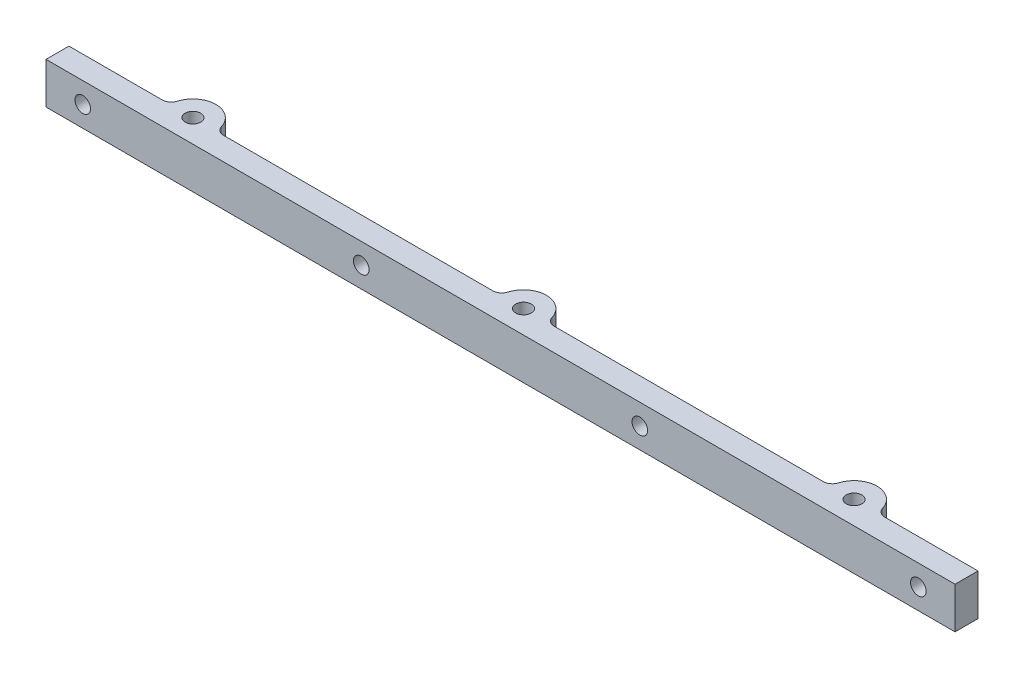
SolidWorks part; units mm, degrees
ref_plane "Plan de face" through (0, 0, 0) normal (0, 0, 1) x (1, 0, 0)
ref_plane "Plan de dessus" through (0, 0, 0) normal (0, 1, 0) x (1, 0, 0)
ref_plane "Plan de droite" through (0, 0, 0) normal (1, 0, 0) x (0, 0, -1)
sketch "Esquisse1" plane through (0, 0, 0) normal (0, 1, 0) x (1, 0, 0)
  line L0 (-99, 2.5) -> (-77, 2.5)
  line L2 (-99, 2.5) -> (-99, -2.5)
  line L3 (-99, -2.5) -> (99, -2.5)
  line L4 (99, 2.5) -> (99, -2.5)
  line L5 (-99, 2.5) -> (99, -2.5) construction
  line L6 (-99, -2.5) -> (99, 2.5) construction
  line L7 (-67, 2.5) -> (-5, 2.5)
  line L8 (5, 2.5) -> (67, 2.5)
  line L9 (77, 2.5) -> (99, 2.5)
  arc A0 (-77, 2.5) -> (-67, 2.5) centre (-72, 2.5) cw
  arc A1 (-5, 2.5) -> (5, 2.5) centre (0, 2.5) cw
  arc A2 (67, 2.5) -> (77, 2.5) centre (72, 2.5) cw
  point P0 (0, 0)
  dimension "D3" = 5
  dimension "D1" = 198
  dimension "D2" = 5
  dimension "D4" = 22
extrude "Boss.-Extru.1" add sketch "Esquisse1" along normal blind 9
hole_wizard "Dégagement M31" positions "Esquisse3" profile "Esquisse4" hole size "M3" standard "Ansi Metric" end condition up to next
sketch "Esquisse3" plane through (0, 9, 0) normal (0, 1, 0) x (1, 0, 0)
  point P0 (-72, 2.5)
  point P3 (0, 2.5)
  point P6 (72, 2.5)
sketch "Esquisse4" plane through (-72, 9, -2.5) normal (1, 0, 0) x (0, 0, 1)
  line L0 (0, 0) -> (0, 9)
  line L1 (0, 9) -> (1.7, 9)
  line L2 (1.7, 9) -> (1.7, 0)
  line L5 (1.7, 0) -> (0, 0)
  line L11 (0, -6.35) -> (0, 107.95) construction
  dimension "Diamètre du perçage jusqu'au prochain" = 3.4
  dimension "Profondeur du perçage jusqu'au prochain" = 9
sketch "Esquisse5" plane through (0, 0, 0) normal (0, -1, 0) x (1, 0, 0)
  line L1 (70.4123, -5.25) -> (73.5877, -5.25)
  line L2 (73.5877, -5.25) -> (75.1754, -2.5)
  line L3 (75.1754, -2.5) -> (73.5877, 0.25)
  line L4 (73.5877, 0.25) -> (70.4123, 0.25)
  line L5 (70.4123, 0.25) -> (68.8246, -2.5)
  line L6 (68.8246, -2.5) -> (70.4123, -5.25)
  line L7 (-1.5877, -5.25) -> (1.5877, -5.25)
  line L8 (1.5877, -5.25) -> (3.1754, -2.5)
  line L9 (3.1754, -2.5) -> (1.5877, 0.25)
  line L10 (1.5877, 0.25) -> (-1.5877, 0.25)
  line L11 (-1.5877, 0.25) -> (-3.1754, -2.5)
  line L12 (-3.1754, -2.5) -> (-1.5877, -5.25)
  line L13 (-73.5877, -5.25) -> (-70.4123, -5.25)
  line L14 (-70.4123, -5.25) -> (-68.8246, -2.5)
  line L15 (-68.8246, -2.5) -> (-70.4123, 0.25)
  line L16 (-70.4123, 0.25) -> (-73.5877, 0.25)
  line L17 (-73.5877, 0.25) -> (-75.1754, -2.5)
  line L18 (-75.1754, -2.5) -> (-73.5877, -5.25)
  circle A0 centre (72, -2.5) radius 2.75 construction
  circle A1 centre (0, -2.5) radius 2.75 construction
  circle A2 centre (-72, -2.5) radius 2.75 construction
  dimension "D1" = 5.5
extrude "Enlèv. mat.-Extru.1" cut sketch "Esquisse5" against normal blind 2.5
sketch "Esquisse6" plane through (0, 0, 2.5) normal (0, 0, 1) x (1, 0, 0)
  line L0 (-99, 0) -> (-91, 4.5) construction
  line L1 (-91, 4.5) -> (-30.3333, 4.5) construction
  line L2 (91, 4.5) -> (99, 0) construction
  line L3 (-30.3333, 4.5) -> (30.3333, 4.5) construction
  line L4 (30.3333, 4.5) -> (91, 4.5) construction
  line L5 (-99, 9) -> (-91, 4.5) construction
  line L6 (-99, 9) -> (-99, 0) construction
  dimension "D1" = 8
hole_wizard "Dégagement M32" positions "Esquisse7" profile "Esquisse8" hole size "M3" standard "Ansi Metric" end condition up to next
sketch "Esquisse7" plane through (0, 0, 2.5) normal (0, 0, 1) x (1, 0, 0)
  point P0 (-91, 4.5)
  point P3 (-30.3333, 4.5)
  point P6 (30.3333, 4.5)
  point P9 (91, 4.5)
sketch "Esquisse8" plane through (-91, 4.5, 2.5) normal (1, 0, 0) x (0, -1, 0)
  line L0 (0, 0) -> (0, 5)
  line L1 (0, 5) -> (1.7, 5)
  line L2 (1.7, 5) -> (1.7, 0)
  line L5 (1.7, 0) -> (0, 0)
  line L11 (0, -6.35) -> (0, 107.95) construction
  dimension "Diamètre du perçage jusqu'au prochain" = 3.4
  dimension "Profondeur du perçage jusqu'au prochain" = 5
sketch "Esquisse9" plane through (0, 0, -2.5) normal (0, 0, -1) x (-1, 0, 0)
  line L1 (-89.4123, 7.25) -> (-92.5877, 7.25)
  line L2 (-92.5877, 7.25) -> (-94.1754, 4.5)
  line L3 (-94.1754, 4.5) -> (-92.5877, 1.75)
  line L4 (-92.5877, 1.75) -> (-89.4123, 1.75)
  line L5 (-89.4123, 1.75) -> (-87.8246, 4.5)
  line L6 (-87.8246, 4.5) -> (-89.4123, 7.25)
  line L7 (-28.7456, 7.25) -> (-31.921, 7.25)
  line L8 (-31.921, 7.25) -> (-33.5088, 4.5)
  line L9 (-33.5088, 4.5) -> (-31.921, 1.75)
  line L10 (-31.921, 1.75) -> (-28.7456, 1.75)
  line L11 (-28.7456, 1.75) -> (-27.1579, 4.5)
  line L12 (-27.1579, 4.5) -> (-28.7456, 7.25)
  line L13 (31.921, 7.25) -> (28.7456, 7.25)
  line L14 (28.7456, 7.25) -> (27.1579, 4.5)
  line L15 (27.1579, 4.5) -> (28.7456, 1.75)
  line L16 (28.7456, 1.75) -> (31.921, 1.75)
  line L17 (31.921, 1.75) -> (33.5088, 4.5)
  line L18 (33.5088, 4.5) -> (31.921, 7.25)
  line L19 (92.5877, 7.25) -> (89.4123, 7.25)
  line L20 (89.4123, 7.25) -> (87.8246, 4.5)
  line L21 (87.8246, 4.5) -> (89.4123, 1.75)
  line L22 (89.4123, 1.75) -> (92.5877, 1.75)
  line L23 (92.5877, 1.75) -> (94.1754, 4.5)
  line L24 (94.1754, 4.5) -> (92.5877, 7.25)
  circle A0 centre (-91, 4.5) radius 2.75 construction
  circle A1 centre (-30.3333, 4.5) radius 2.75 construction
  circle A2 centre (30.3333, 4.5) radius 2.75 construction
  circle A3 centre (91, 4.5) radius 2.75 construction
  dimension "D1" = 5.5
extrude "Enlèv. mat.-Extru.2" cut sketch "Esquisse9" against normal blind 2.5
fillet "Congé1" radius 2 6 edges at (-77, 4.5, -2.5) (-67, 4.5, -2.5) (-5, 4.5, -2.5) (5, 4.5, -2.5) (67, 4.5, -2.5) (77, 4.5, -2.5)
